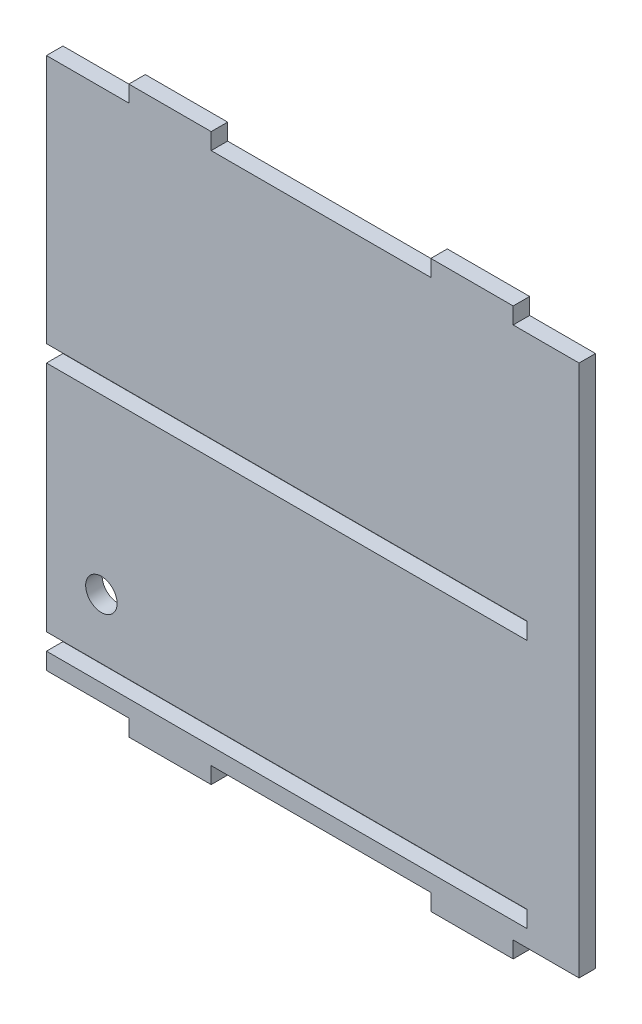
SolidWorks part; units mm, degrees
ref_plane "Plano frontal" through (0, 0, 0) normal (0, 0, 1) x (1, 0, 0)
ref_plane "Plano superior" through (0, 0, 0) normal (0, 1, 0) x (1, 0, 0)
ref_plane "Plano direito" through (0, 0, 0) normal (1, 0, 0) x (0, 0, -1)
sketch "Esboço1" plane through (0, 0, 0) normal (0, 0, 1) x (1, 0, 0)
  line L0 (-67, -97) -> (-97, -97)
  line L2 (-97, 97) -> (-97, -97)
  line L4 (97, 97) -> (97, -97)
  line L5 (-97, 97) -> (97, -97) construction
  line L6 (-97, -97) -> (97, 97) construction
  line L8 (-67, -97) -> (-67, -103)
  line L9 (-67, -103) -> (-37, -103)
  line L10 (-37, -97) -> (-37, -103)
  line L12 (43, -97) -> (43, -103)
  line L13 (43, -103) -> (73, -103)
  line L14 (73, -97) -> (73, -103)
  line L15 (-37, -97) -> (43, -97)
  line L16 (73, -97) -> (97, -97)
  line L17 (-67, 97) -> (-97, 97)
  line L19 (-67, 97) -> (-67, 103)
  line L20 (-67, 103) -> (-37, 103)
  line L21 (-37, 97) -> (-37, 103)
  line L23 (43, 97) -> (43, 103)
  line L24 (43, 103) -> (73, 103)
  line L25 (73, 97) -> (73, 103)
  line L26 (-37, 97) -> (43, 97)
  line L27 (73, 97) -> (97, 97)
  point P0 (0, 0)
  dimension "D1" = 194
  dimension "D2" = 194
  dimension "D3" = 30
  dimension "D4" = 30
  dimension "D5" = 6
  dimension "D6" = 6
  dimension "D7" = 30
  dimension "D8" = 24
  dimension "D9" = 6
  dimension "D10" = 6
  dimension "D11" = 6
  dimension "D12" = 30
  dimension "D13" = 24
  dimension "D14" = 6
  dimension "D15" = 30
  dimension "D16" = 30
  dimension "D17" = 6
  dimension "D18" = 6
extrude "Ressalto-extrusão1" add sketch "Esboço1" along normal blind 6
sketch "Esboço2" plane through (0, 0, 6) normal (0, 0, 1) x (1, 0, 0)
  line L0 (-97, 97) -> (-97, -97) construction
  line L1 (-97, 0) -> (78, 0)
  line L2 (-97, 0) -> (-97, 6.1)
  line L3 (-97, 6.1) -> (78, 6.1)
  line L4 (78, 0) -> (78, 6.1)
  line L6 (-97, -97) -> (-67, -97) construction
  line L7 (-97, -90.9) -> (78, -90.9)
  line L8 (-97, -90.9) -> (-97, -84.8)
  line L9 (-97, -84.8) -> (78, -84.8)
  line L10 (78, -90.9) -> (78, -84.8)
  dimension "D1" = 6.1
  dimension "D2" = 175
  dimension "D3" = 6.1
  dimension "D4" = 175
  dimension "D5" = 6.1
extrude "Corte-extrusão1" cut sketch "Esboço2" against normal blind 10
sketch "Esboço3" plane through (0, 0, 6) normal (0, 0, 1) x (1, 0, 0)
  line L0 (-97, 0) -> (-97, -84.8) construction
  line L1 (-67, -103) -> (-37, -103) construction
  circle A0 centre (-77, -63) radius 5.725
  dimension "D3" = 11.45
  dimension "D1" = 20
  dimension "D2" = 40
extrude "Corte-extrusão2" cut sketch "Esboço3" against normal blind 10
